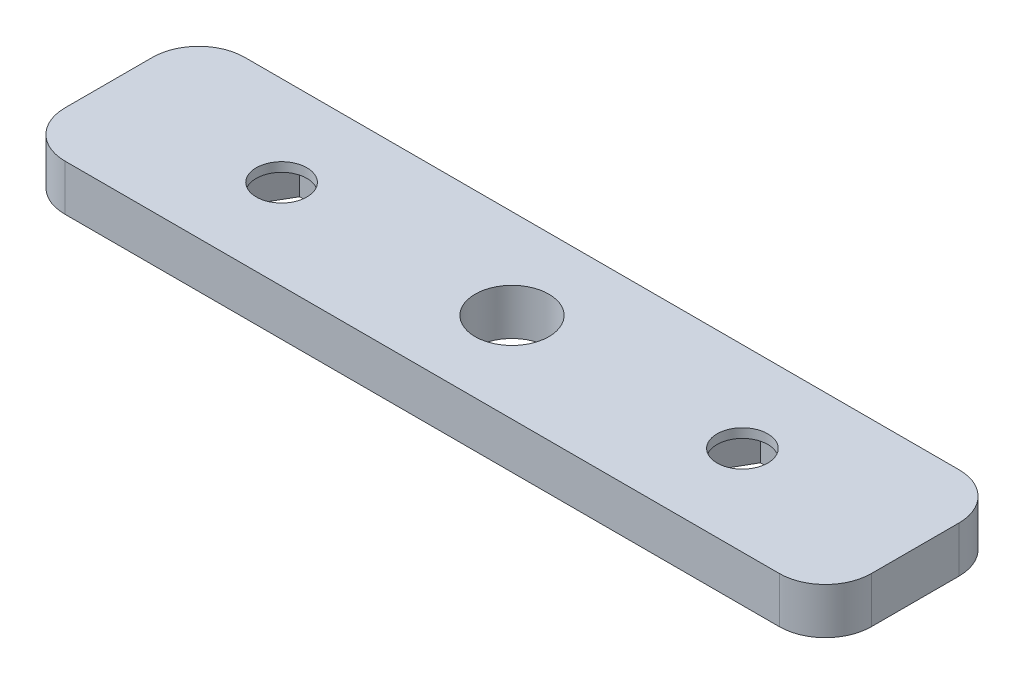
SolidWorks part; units mm, degrees
ref_plane "Alzado" through (0, 0, 0) normal (0, 0, 1) x (1, 0, 0)
ref_plane "Planta" through (0, 0, 0) normal (0, 1, 0) x (1, 0, 0)
ref_plane "Vista lateral" through (0, 0, 0) normal (1, 0, 0) x (0, 0, -1)
sketch "Croquis1" plane through (0, 0, 0) normal (0, 1, 0) x (1, 0, 0)
  line L1 (-35, -7.8) -> (35, -7.8)
  line L2 (-35, -7.8) -> (-35, 7.8)
  line L3 (-35, 7.8) -> (35, 7.8)
  line L4 (35, -7.8) -> (35, 7.8)
  line L5 (-35, -7.8) -> (35, 7.8) construction
  line L6 (-35, 7.8) -> (35, -7.8) construction
  point P0 (0, 0)
  dimension "D1" = 15.6
  dimension "D2" = 70
extrude "Saliente-Extruir1" add sketch "Croquis1" along normal blind 4
sketch "Croquis3" plane through (0, 0, 0) normal (0, 1, 0) x (1, 0, 0)
  line L0 (-2.2, 0) -> (2.2, 0) construction
  line L1 (0, -2.2) -> (0, 2.2) construction
  circle A0 centre (0, 0) radius 3.2
  circle A1 centre (20, 0) radius 2.2
  circle A2 centre (-20, 0) radius 2.2
  dimension "D1" = 6.4
  dimension "D2" = 4.4
  dimension "D3" = 40
extrude "Cortar-Extruir2" cut sketch "Croquis3" along normal through all both and the other way through all
fillet "Redondeo1" radius 4 4 edges at (35, 2, -7.8) (35, 2, 7.8) (-35, 2, 7.8) (-35, 2, -7.8)
sketch "Croquis5" plane through (0, 0, 0) normal (0, 1, 0) x (1, 0, 0)
  line L0 (0, -2.2) -> (0, 2.2) construction
  line L1 (-15.7276, 0) -> (-17.8638, 3.7)
  line L2 (-17.8638, 3.7) -> (-22.1362, 3.7)
  line L3 (-22.1362, 3.7) -> (-24.2724, 0)
  line L4 (-24.2724, 0) -> (-22.1362, -3.7)
  line L5 (-22.1362, -3.7) -> (-17.8638, -3.7)
  line L6 (-17.8638, -3.7) -> (-15.7276, 0)
  line L7 (17.8638, -3.7) -> (15.7276, 0)
  line L8 (22.1362, -3.7) -> (17.8638, -3.7)
  line L9 (24.2724, 0) -> (22.1362, -3.7)
  line L10 (22.1362, 3.7) -> (24.2724, 0)
  line L11 (17.8638, 3.7) -> (22.1362, 3.7)
  line L12 (15.7276, 0) -> (17.8638, 3.7)
  circle A0 centre (-20, 0) radius 3.7 construction
  circle A1 centre (20, 0) radius 3.7 construction
  dimension "D1" = 7.4
extrude "Cortar-Extruir4" cut sketch "Croquis5" along normal blind 3.2
